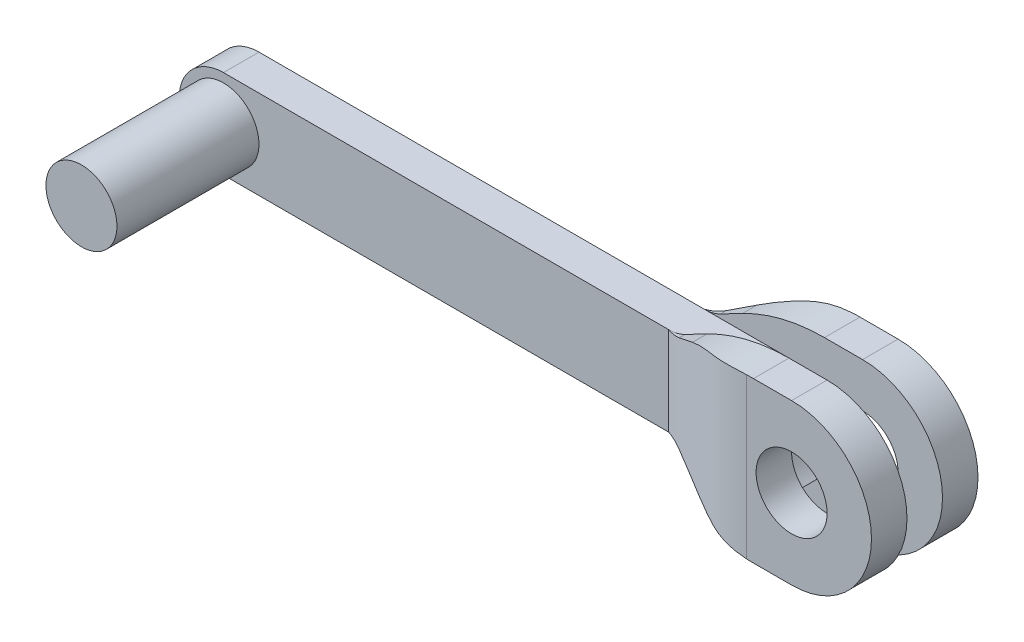
SolidWorks part; units mm, degrees
ref_plane "Front Plane" through (0, 0, 0) normal (0, 0, 1) x (1, 0, 0)
ref_plane "Top Plane" through (0, 0, 0) normal (0, 1, 0) x (1, 0, 0)
ref_plane "Right Plane" through (0, 0, 0) normal (1, 0, 0) x (0, 0, -1)
sketch "Sketch1" plane through (0, 0, 0) normal (0, 0, 1) x (1, 0, 0)
  line L0 (0, -2.5) -> (34, -2.5)
  line L3 (0, 2.5) -> (34, 2.5)
  arc A0 (0, 2.5) -> (0, -2.5) centre (0, 0) ccw
  arc A1 (34, -2.5) -> (34, 2.5) centre (34, 0) ccw
  dimension "D2" = 5
  dimension "D1" = 34
extrude "Boss-Extrude1" add sketch "Sketch1" along normal blind 2
sketch "Sketch2" plane through (0, 0, 2) normal (0, 0, 1) x (1, 0, 0)
  circle A0 centre (0, 0) radius 2
  dimension "D1" = 4
extrude "Boss-Extrude2" add sketch "Sketch2" along normal blind 8
sketch "Sketch5" plane through (0, 0, 0) normal (0, 0, -1) x (-1, 0, 0)
  circle A1 centre (-34, 0) radius 3.5
  dimension "D1" = 7
extrude "Cut-Extrude2" cut sketch "Sketch5" against normal mid plane 10
sketch "Sketch3" plane through (0, 0, 0) normal (0, 0, -1) x (-1, 0, 0)
  line L0 (-34, -4.5) -> (-31.854, -4.5)
  line L2 (-31.854, 4.5) -> (-34, 4.5)
  line L3 (-27.2347, -3.3692) -> (-26.0001, -2.7262)
  line L5 (-27.2347, 3.3692) -> (-26.0001, 2.7262)
  line L7 (-25.0763, -2.5) -> (-25.0763, 2.5)
  arc A0 (-34, 4.5) -> (-34, -4.5) centre (-34, 0) ccw
  arc A1 (-31.854, -4.5) -> (-27.2347, -3.3692) centre (-31.854, 5.5) ccw
  arc A4 (-27.2347, 3.3692) -> (-31.854, 4.5) centre (-31.854, -5.5) ccw
  arc A5 (-25.0763, 2.5) -> (-26.0001, 2.7262) centre (-25.0763, 4.5) cw
  arc A6 (-25.0763, -2.5) -> (-26.0001, -2.7262) centre (-25.0763, -4.5) ccw
  dimension "D2" = 10
  dimension "D3" = 2
  dimension "D4" = 2
extrude "Boss-Extrude3" add sketch "Sketch3" along normal blind 2
sketch "Sketch4" plane through (0, 0, 0) normal (0, 1, 0) x (1, 0, 0)
  line L0 (31.854, 2) -> (31.854, 3.1743)
  line L1 (31.854, 3.1743) -> (24.3839, 3.1743)
  line L2 (24.3839, 3.1743) -> (25.0763, 0)
  spline S0 degree 3 poles (31.854, 2) (29.9625, 2.0207) (29.1699, 1.6051) (25.9668, 0.2836) (25.0763, 0) knots 0 0 0 0 0.608349 1 1 1 1
extrude "Cut-Extrude1" cut sketch "Sketch4" against normal mid plane 11
ref_plane "Plane1" through (0, 0, 1) normal (0, 0, 1) x (1, 0, 0)
mirror "Mirror1" about plane through (0, 0, 1) normal (0, 0, 1) of "Cut-Extrude1", "Boss-Extrude3"
sketch "Sketch6" plane through (0, 0, -2) normal (0, 0, -1) x (-1, 0, 0)
  circle A0 centre (-34, 0) radius 2
  dimension "D1" = 4
extrude "Cut-Extrude3" cut sketch "Sketch6" against normal mid plane 22
